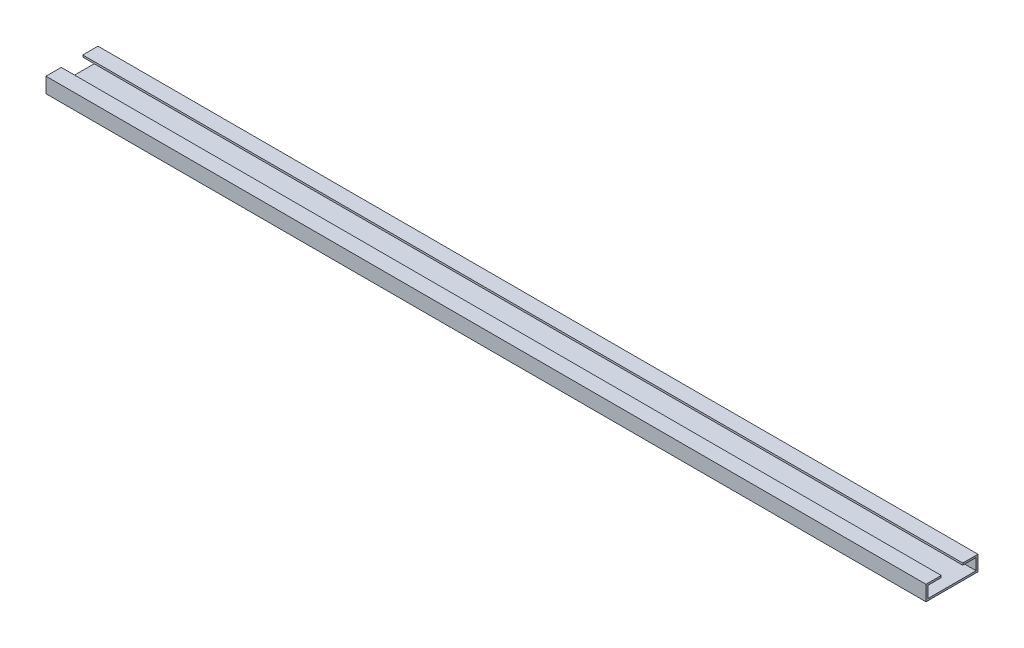
SolidWorks part; units mm, degrees
ref_plane "Ön Düzlem" through (0, 0, 0) normal (0, 0, 1) x (1, 0, 0)
ref_plane "Üst Düzlem" through (0, 0, 0) normal (0, 1, 0) x (1, 0, 0)
ref_plane "Sağ Düzlem" through (0, 0, 0) normal (1, 0, 0) x (0, 0, -1)
ref_plane "Düzlem1" through (0, 0, 0) normal (-1, 0, 0) x (0, -1, 0)
sketch "Çizim1" plane through (0, 0, 0) normal (-1, 0, 0) x (0, -1, 0)
  line L0 (0, 0) -> (-4, 0)
  line L1 (-4, 0) -> (-4, -4)
  line L2 (-4, -4) -> (-3.5, -4)
  line L3 (-3.5, -4) -> (-3.5, -0.5)
  line L4 (-3.5, -0.5) -> (-0.5, -0.5)
  line L5 (-0.5, -0.5) -> (-0.5, -13.15)
  line L6 (-0.5, -13.15) -> (-3.5, -13.15)
  line L7 (-3.5, -13.15) -> (-3.5, -9.65)
  line L8 (-3.5, -9.65) -> (-4, -9.65)
  line L9 (-4, -9.65) -> (-4, -13.65)
  line L10 (-4, -13.65) -> (0, -13.65)
  line L11 (0, -13.65) -> (0, 0)
extrude "Yükseklik-Ekstrüzyon1" add sketch "Çizim1" against normal blind 370
sketch "Çizim3" plane through (0, 0, 0) normal (-1, 0, 0) x (0, 0, 1)
  line L0 (-13.65, 0) -> (-13.65, 4)
  line L1 (-13.65, 4) -> (-9.65, 4)
  line L2 (-9.65, 4) -> (-9.65, 3.5)
  line L3 (-9.65, 3.5) -> (-13.15, 3.5)
  line L4 (-13.15, 3.5) -> (-9.65, 3.5) construction
  line L5 (-13.15, 3.5) -> (-13.15, 0.5)
  line L6 (-13.15, 0.5) -> (-0.5, 0.5)
  line L7 (-0.5, 0.5) -> (-0.5, 3.5)
  line L8 (-0.5, 3.5) -> (-4, 3.5)
  line L9 (-4, 3.5) -> (-4, 4)
  line L10 (-4, 4) -> (0, 4)
  line L11 (0, 4) -> (0, 0)
  line L12 (0, 0) -> (-13.65, 0)
extrude "Yükseklik-Ekstrüzyon2" add sketch "Çizim3" against normal blind 141 and the other way blind 2
sketch "Çizim5" plane through (-2, 0, 0) normal (-1, 0, 0) x (0, 0, 1)
  line L0 (-13.65, 4) -> (-13.65, 0)
  line L1 (-13.65, 0) -> (0, 0)
  line L2 (0, 0) -> (0, 4)
  line L3 (0, 4) -> (-4, 4)
  line L4 (-4, 4) -> (-4, 3.5)
  line L5 (-4, 3.5) -> (-0.5, 3.5)
  line L6 (-0.5, 3.5) -> (-0.5, 0.5)
  line L7 (-0.5, 0.5) -> (-13.15, 0.5)
  line L8 (-13.15, 0.5) -> (-13.15, 3.5)
  line L9 (-13.15, 3.5) -> (-9.65, 3.5)
  line L10 (-13.15, 3.5) -> (-9.65, 3.5) construction
  line L11 (-9.65, 3.5) -> (-9.65, 4)
  line L12 (-9.65, 4) -> (-13.65, 4) construction
  line L13 (-9.65, 4) -> (-13.65, 4)
extrude "Kes-Ekstrüzyon1" cut sketch "Çizim5" against normal blind 141
